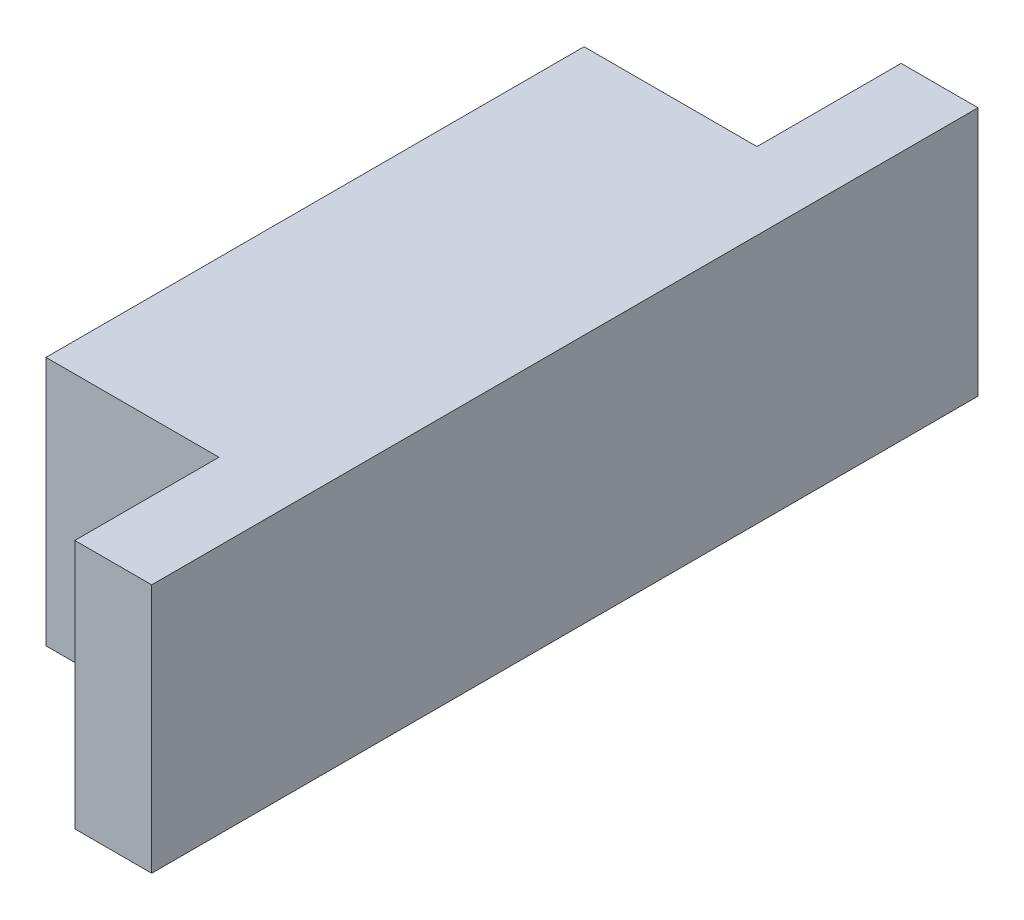
SolidWorks part; units mm, degrees
ref_plane "Front" through (0, 0, 0) normal (0, 0, 1) x (1, 0, 0)
ref_plane "Top" through (0, 0, 0) normal (0, 1, 0) x (1, 0, 0)
ref_plane "Right" through (0, 0, 0) normal (1, 0, 0) x (0, 0, -1)
sketch "Croquis1" plane through (0, 0, 0) normal (1, 0, 0) x (0, 0, -1)
  line L1 (0, 0) -> (28, 0)
  line L2 (0, 0) -> (0, 13)
  line L3 (0, 13) -> (28, 13)
  line L4 (28, 0) -> (28, 13)
  line L5 (0, 0) -> (28, 13) construction
  line L6 (0, 13) -> (28, 0) construction
  point P4 (14, 6.5)
  dimension "D1" = 13
  dimension "D2" = 28
extrude "Saliente-Extruir1" add sketch "Croquis1" along normal blind 9
sketch "Croquis2" plane through (9, 0, 0) normal (1, 0, 0) x (0, 0, -1)
  line L0 (0, 0) -> (28, 0) construction
  line L1 (-7.5, 13) -> (35.5, 13)
  line L2 (-7.5, 13) -> (-7.5, 0)
  line L3 (-7.5, 0) -> (35.5, 0)
  line L4 (35.5, 13) -> (35.5, 0)
  line L5 (-7.5, 13) -> (35.5, 0) construction
  line L6 (-7.5, 0) -> (35.5, 13) construction
  line L7 (0, 13) -> (0, 0) construction
  point P0 (14, 6.5)
  point P5 (20.6693, 14.4496)
  point P8 (0, 0)
  point P9 (14, 0)
  point P12 (0, 6.5)
  dimension "D1" = 43
  dimension "D2" = 13
extrude "Saliente-Extruir2" add sketch "Croquis2" along normal blind 4
